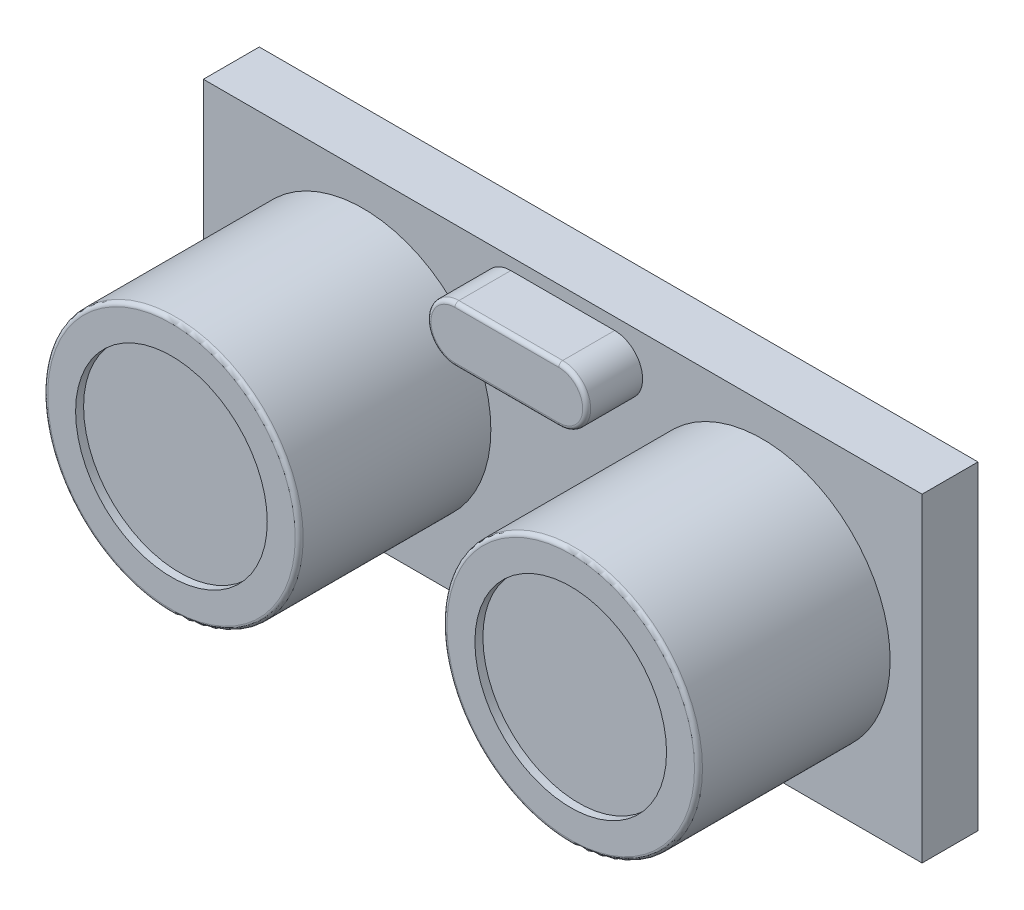
SolidWorks part; units mm, degrees
ref_plane "Front Plane" through (0, 0, 0) normal (0, 0, 1) x (1, 0, 0)
ref_plane "Top Plane" through (0, 0, 0) normal (0, 1, 0) x (1, 0, 0)
ref_plane "Right Plane" through (0, 0, 0) normal (1, 0, 0) x (0, 0, -1)
sketch "Sketch1" plane through (0, 0, 0) normal (0, 0, 1) x (1, 0, 0)
  line L1 (-22.5, 10) -> (22.5, 10)
  line L2 (-22.5, 10) -> (-22.5, -10)
  line L3 (-22.5, -10) -> (22.5, -10)
  line L4 (22.5, 10) -> (22.5, -10)
  line L5 (-22.5, 10) -> (22.5, -10) construction
  line L6 (-22.5, -10) -> (22.5, 10) construction
  point P0 (0, 0)
  dimension "D1" = 20
  dimension "D2" = 45
extrude "Boss-Extrude1" add sketch "Sketch1" along normal blind 3.5
sketch "Sketch2" plane through (0, 0, 3.5) normal (0, 0, 1) x (1, 0, 0)
  line L0 (-22.5, -10) -> (22.5, -10) construction
  line L1 (-22.5, 10) -> (-12.5, 10) construction
  line L2 (-22.5, 10) -> (-22.5, -10) construction
  line L3 (-22.5, -10) -> (-12.5, -10) construction
  line L4 (-12.5, 10) -> (-12.5, -10) construction
  line L6 (22.5, 10) -> (12.5, 10) construction
  line L7 (22.5, 10) -> (22.5, -10) construction
  line L8 (22.5, -10) -> (12.5, -10) construction
  line L9 (12.5, 10) -> (12.5, -10) construction
  circle A0 centre (12.5, 0) radius 8
  circle A1 centre (-12.5, 0) radius 8
  point P17 (-12.5, 0)
  point P19 (12.5, 0)
  dimension "D1" = 16
  dimension "D2" = 10
extrude "Boss-Extrude2" add sketch "Sketch2" along normal blind 12
sketch "Sketch3" plane through (0, 0, 15.5) normal (0, 0, 1) x (1, 0, 0)
  circle A0 centre (-12.5, 0) radius 6
  circle A1 centre (12.5, 0) radius 6
  circle A2 centre (12.5, 0) radius 8 construction
  circle A3 centre (-12.5, 0) radius 8 construction
  dimension "D1" = 2
extrude "Cut-Extrude1" cut sketch "Sketch3" against normal blind 0.5
fillet "Fillet1" radius 0.25 2 edges at (20.5, 0, 15.5) (-4.5, 0, 15.5)
sketch "Sketch4" plane through (0, 0, 3.5) normal (0, 0, 1) x (1, 0, 0)
  line L0 (-3.25, 7.5) -> (3.25, 7.5) construction
  line L1 (-3.25, 9.25) -> (3.25, 9.25)
  line L2 (-3.25, 5.75) -> (3.25, 5.75)
  line L3 (22.5, 10) -> (-22.5, 10) construction
  arc A0 (-3.25, 9.25) -> (-3.25, 5.75) centre (-3.25, 7.5) ccw
  arc A1 (3.25, 5.75) -> (3.25, 9.25) centre (3.25, 7.5) ccw
  point P2 (0, 7.5)
  dimension "D1" = 3.5
  dimension "D2" = 6.5
  dimension "D3" = 2.5
extrude "Boss-Extrude3" add sketch "Sketch4" along normal blind 3.5
fillet "Fillet2" radius 0.25 4 edges at (0, 9.25, 7) (5, 7.5, 7) (0, 5.75, 7) (-5, 7.5, 7)
